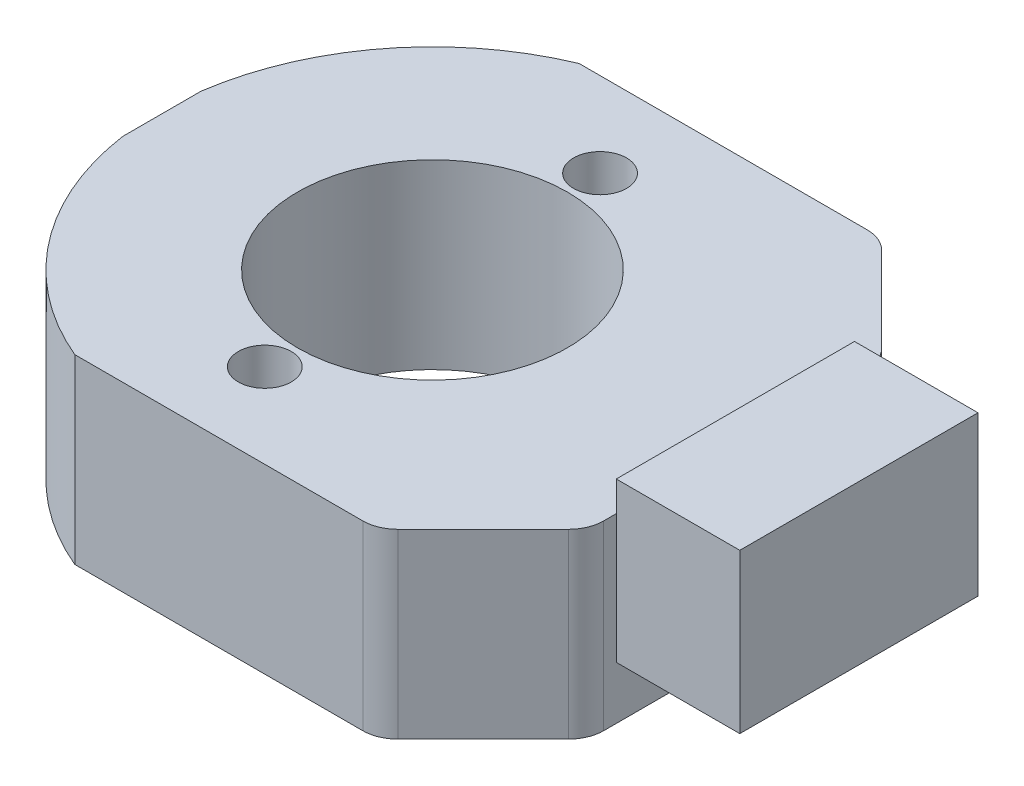
SolidWorks part; units mm, degrees
ref_plane "正面" through (0, 0, 0) normal (0, 0, 1) x (1, 0, 0)
ref_plane "平面" through (0, 0, 0) normal (0, 1, 0) x (1, 0, 0)
ref_plane "右側面" through (0, 0, 0) normal (1, 0, 0) x (0, 0, -1)
sketch "ｽｹｯﾁ1" plane through (0, 0, 0) normal (0, 1, 0) x (1, 0, 0)
  line L1 (-15.33, 14.29) -> (17.17, 14.29)
  line L2 (-15.33, 14.29) -> (-15.33, -14.29)
  line L3 (-15.33, -14.29) -> (17.17, -14.29)
  line L4 (17.17, 14.29) -> (17.17, -14.29)
  circle A0 centre (0, 0) radius 7.65
  arc A2 (-5.978, 14.29) -> (-15.33, 2.2206) centre (0, 0) ccw
  arc A3 (-15.33, -2.2206) -> (-5.978, -14.29) centre (0, 0) ccw
  point P7 (-15.33, 0)
  dimension "D1" = 15.3
  dimension "D5" = 30.98
  dimension "D2" = 28.58
  dimension "D3" = 32.5
  dimension "D4" = 15.33
extrude "ﾎﾞｽ - 押し出し1" add sketch "ｽｹｯﾁ1" along normal blind 10.3
sketch "ｽｹｯﾁ2" plane through (0, 0, 0) normal (0, -1, 0) x (1, 0, 0)
  line L0 (0, -14.29) -> (0, 14.29) construction
  line L1 (-5.978, -14.29) -> (17.17, -14.29) construction
  line L2 (-5.978, 14.29) -> (17.17, 14.29) construction
  line L3 (0, 0) -> (17.17, 0) construction
  line L4 (17.17, -14.29) -> (17.17, 14.29) construction
  circle A0 centre (0, 9.5) radius 1.5
  circle A1 centre (0, -9.5) radius 1.5
  circle A2 centre (0, 0) radius 8 construction
  circle A3 centre (0, 0) radius 11 construction
  dimension "D4" = 16
  dimension "D5" = 22
  dimension "D3" = 0
extrude "ｶｯﾄ - 押し出し1" cut sketch "ｽｹｯﾁ2" against normal blind 10.5
chamfer "面取り1" distance 6 angle 45 2 edges at (17.17, 5.15, -14.29) (17.17, 5.15, 14.29)
fillet "ﾌｨﾚｯﾄ1" radius 2 4 edges at (11.17, 5.15, -14.29) (17.17, 5.15, -8.29) (17.17, 5.15, 8.29) (11.17, 5.15, 14.29)
sketch "ｽｹｯﾁ4" plane through (0, 0, 0) normal (0, 1, 0) x (1, 0, 0)
  line L0 (17.17, 14.29) -> (17.17, -14.29) construction
  line L1 (17.17, 6.75) -> (24.17, 6.75)
  line L2 (17.17, 6.75) -> (17.17, -6.75)
  line L3 (17.17, -6.75) -> (24.17, -6.75)
  line L4 (24.17, 6.75) -> (24.17, -6.75)
  point P6 (24.17, 0)
  dimension "D1" = 13.5
  dimension "D2" = 7
extrude "ﾎﾞｽ - 押し出し2" add sketch "ｽｹｯﾁ4" along normal blind 9 from offset 3
